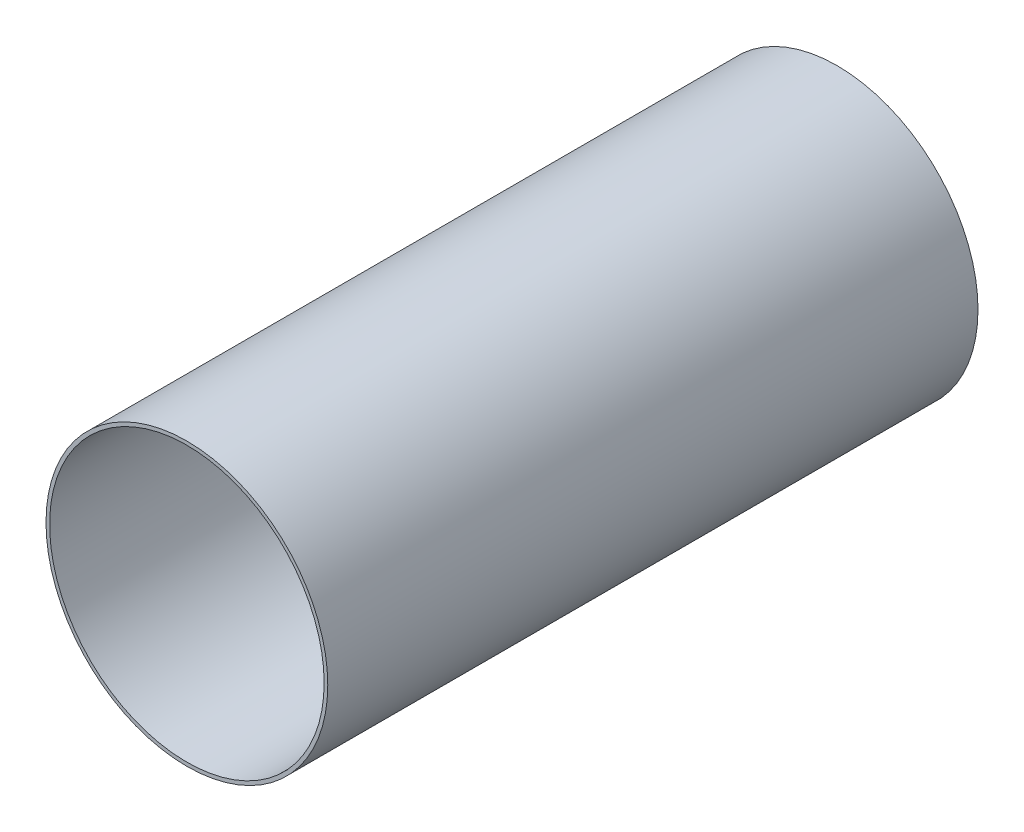
SolidWorks part; units mm, degrees
ref_plane "Front Plane" through (0, 0, 0) normal (0, 0, 1) x (1, 0, 0)
ref_plane "Top Plane" through (0, 0, 0) normal (0, 1, 0) x (1, 0, 0)
ref_plane "Right Plane" through (0, 0, 0) normal (1, 0, 0) x (0, 0, -1)
sketch "Sketch1" plane through (0, 0, 0) normal (0, 0, 1) x (1, 0, 0)
  circle A0 centre (0, 0) radius 49.53
  circle A1 centre (0, 0) radius 48.26
  dimension "D1" = 99.06
  dimension "D2" = 96.52
extrude "Boss-Extrude1" add sketch "Sketch1" along normal blind 228.6
